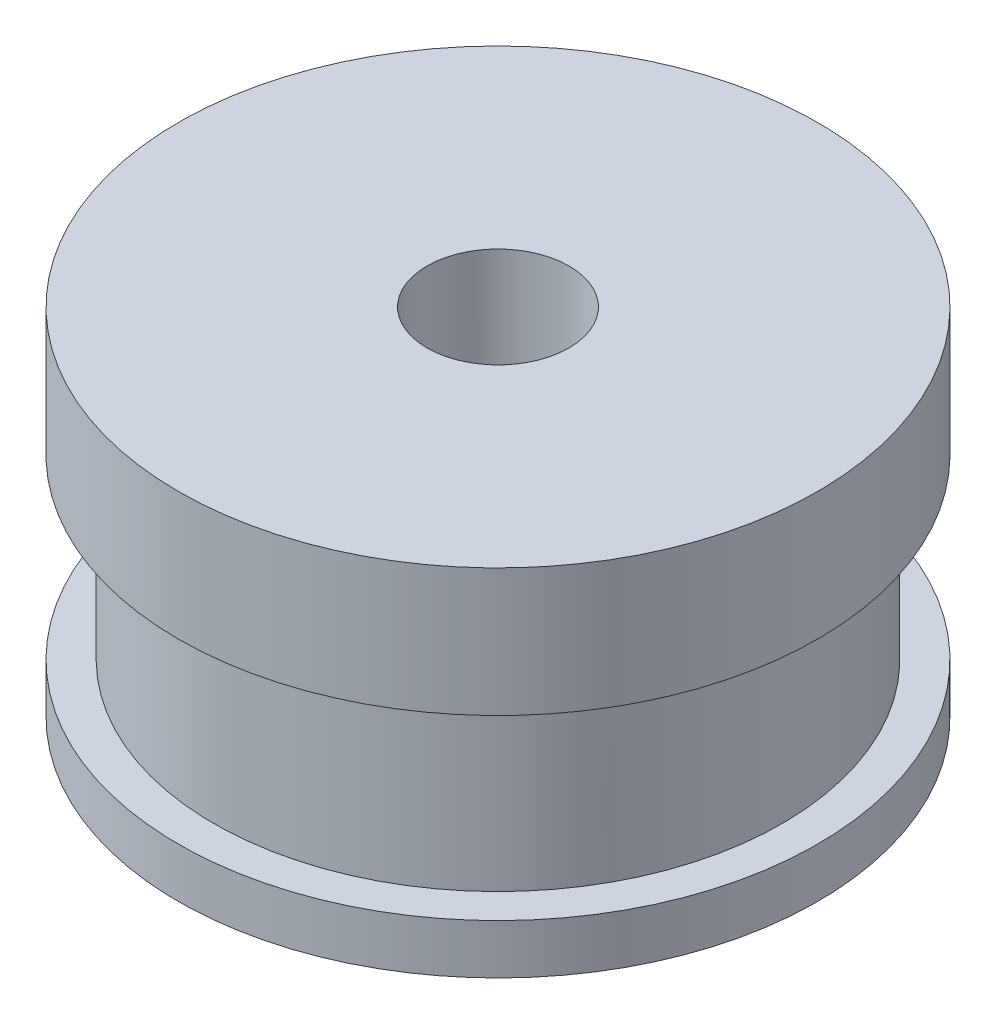
SolidWorks part; units mm, degrees
ref_plane "Plan de face" through (0, 0, 0) normal (0, 0, 1) x (1, 0, 0)
ref_plane "Plan de dessus" through (0, 0, 0) normal (0, 1, 0) x (1, 0, 0)
ref_plane "Plan de droite" through (0, 0, 0) normal (1, 0, 0) x (0, 0, -1)
sketch "Esquisse1" plane through (0, 0, 0) normal (0, 1, 0) x (1, 0, 0)
  circle A0 centre (0, 0) radius 4
extrude "Boss.-Extru.1" add sketch "Esquisse1" along normal mid plane 2.5
sketch "Esquisse2" plane through (0, 1.25, 0) normal (0, 1, 0) x (1, 0, 0)
  circle A0 centre (0, 0) radius 4.5
extrude "Boss.-Extru.2" add sketch "Esquisse2" along normal blind 1.8
sketch "Esquisse3" plane through (0, -1.25, 0) normal (0, -1, 0) x (-1, 0, 0)
  circle A0 centre (0, 0) radius 4.5
extrude "Boss.-Extru.3" add sketch "Esquisse3" along normal blind 0.7
hole_wizard "Perçage1" positions "Esquisse5" profile "Esquisse4" legacy
sketch "Esquisse5" plane through (0, -1.95, 0) normal (0, -1, 0) x (-1, 0, 0)
  point P0 (0, 0)
sketch "Esquisse4" plane through (0, -1.95, 0) normal (1, 0, 0) x (0, 0, -1)
  line L0 (0, 0) -> (0, 10.6009)
  line L1 (0, 10.6009) -> (1, 10)
  line L2 (1, 10) -> (1, 1.6009)
  line L3 (1, 1.6009) -> (2, 1)
  line L4 (2, 1) -> (2, 0)
  line L5 (2, 0) -> (0, 0)
  line L6 (0, -6.13) -> (0, 109.2824) construction
  line L7 (-1, 1.6009) -> (-2, 1) construction
  line L8 (0, 10.6009) -> (-1, 10) construction
  dimension "Diamètre" = 2
  dimension "Profondeur" = 10
  dimension "Diamètre contre-pointe" = 4
  dimension "Profondeur contre-pointe" = 1
  dimension "Angle" = 118
  dimension "Angle contre-pointe" = 118
